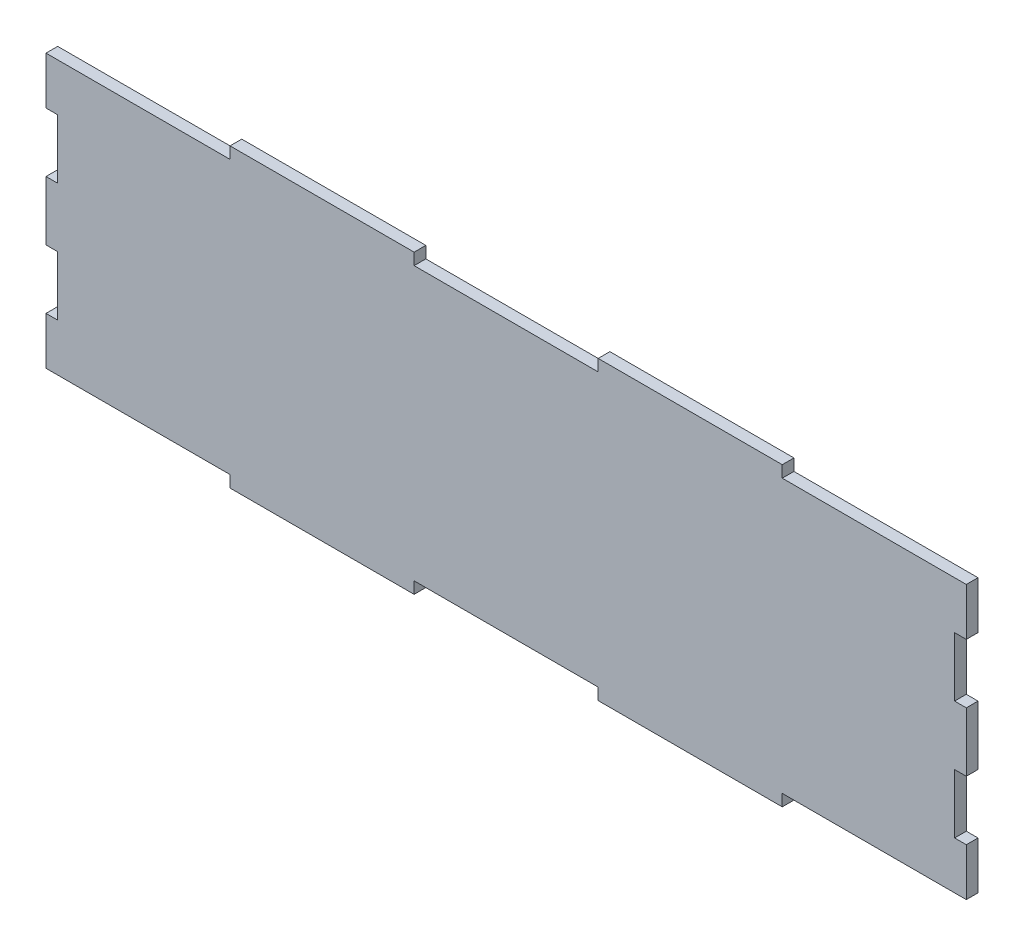
SolidWorks part; units mm, degrees
material "Pin"
ref_plane "Plan de face" through (0, 0, 0) normal (0, 0, 1) x (1, 0, 0)
ref_plane "Plan de dessus" through (0, 0, 0) normal (0, 1, 0) x (1, 0, 0)
ref_plane "Plan de droite" through (0, 0, 0) normal (1, 0, 0) x (0, 0, -1)
sketch "Esquisse1" plane through (0, 0, 0) normal (0, 0, 1) x (1, 0, 0)
  line L0 (-101.9585, 39.1998) -> (-57.7585, 39.1998)
  line L1 (-57.7585, 42.1998) -> (-10.5585, 42.1998)
  line L3 (-57.7585, -33.8002) -> (-10.5585, -33.8002)
  line L5 (128.0415, 26.9998) -> (128.0415, 11.7998)
  line L6 (-101.9585, -30.8002) -> (-57.7585, -30.8002)
  line L7 (-101.9585, 26.9998) -> (-101.9585, 11.7998)
  line L8 (-57.7585, 42.1998) -> (-57.7585, 39.1998)
  line L9 (-10.5585, -30.8002) -> (36.6415, -30.8002)
  line L10 (-10.5585, 42.1998) -> (-10.5585, 39.1998)
  line L11 (-104.9585, -33.8002) -> (131.0415, -33.8002) construction
  line L12 (36.6415, 42.1998) -> (36.6415, 39.1998)
  line L13 (36.6415, -33.8002) -> (83.8415, -33.8002)
  line L14 (83.8415, 42.1998) -> (83.8415, 39.1998)
  line L15 (-101.9585, -30.8002) -> (128.0415, -30.8002) construction
  line L16 (-104.9585, 26.9998) -> (-101.9585, 26.9998)
  line L17 (-104.9585, 11.7998) -> (-101.9585, 11.7998)
  line L18 (83.8415, -30.8002) -> (83.8415, -33.8002)
  line L19 (83.8415, -30.8002) -> (128.0415, -30.8002)
  line L20 (36.6415, -30.8002) -> (36.6415, -33.8002)
  line L21 (-104.9585, -33.8002) -> (-57.7585, -33.8002) construction
  line L22 (-10.5585, -30.8002) -> (-10.5585, -33.8002)
  line L23 (-57.7585, -30.8002) -> (-57.7585, -33.8002)
  line L24 (83.8415, -33.8002) -> (131.0415, -33.8002) construction
  line L25 (128.0415, 26.9998) -> (131.0415, 26.9998)
  line L26 (128.0415, 11.7998) -> (131.0415, 11.7998)
  line L27 (-104.9585, -3.4002) -> (-101.9585, -3.4002)
  line L28 (128.0415, -3.4002) -> (131.0415, -3.4002)
  line L29 (-104.9585, -18.6002) -> (-101.9585, -18.6002)
  line L30 (128.0415, -18.6002) -> (131.0415, -18.6002)
  line L31 (-104.9585, 26.9998) -> (-104.9585, 11.7998) construction
  line L32 (-34.1585, 47.9048) -> (-34.1585, 44.9048) [skipped]
  line L33 (13.0415, 47.9048) -> (13.0415, 44.9048) [skipped]
  line L34 (60.2415, 47.9048) -> (60.2415, 44.9048) [skipped]
  line L35 (-10.5585, 39.1998) -> (36.6415, 39.1998)
  line L36 (36.6415, 42.1998) -> (83.8415, 42.1998)
  line L37 (-101.9585, 39.1998) -> (128.0415, 39.1998) construction
  line L38 (83.8415, 39.1998) -> (128.0415, 39.1998)
  line L39 (-104.9585, 42.1998) -> (131.0415, 42.1998) construction
  line L40 (-57.7585, 42.1998) -> (-104.9585, 42.1998) construction
  line L41 (83.8415, 42.1998) -> (131.0415, 42.1998) construction
  line L42 (-104.9585, 11.7998) -> (-104.9585, -3.4002)
  line L43 (-101.9585, -3.4002) -> (-101.9585, -18.6002)
  line L44 (-104.9585, 42.1998) -> (-104.9585, -33.8002) construction
  line L46 (-101.9585, 39.1998) -> (-101.9585, -30.8002) construction
  line L47 (-101.9585, -30.8002) -> (-104.9585, -30.8002)
  line L48 (-104.9585, 42.1998) -> (-104.9585, 26.9998) construction
  line L49 (-104.9585, -18.6002) -> (-104.9585, -33.8002) construction
  line L50 (-104.9585, 26.9998) -> (-104.9585, 39.1998)
  line L51 (-104.9585, 39.1998) -> (-101.9585, 39.1998)
  line L52 (-104.9585, -30.8002) -> (-104.9585, -18.6002)
  line L53 (131.0415, 11.7998) -> (131.0415, -3.4002)
  line L54 (128.0415, 39.1998) -> (131.0415, 39.1998)
  line L55 (131.0415, 42.1998) -> (131.0415, -33.8002) construction
  line L56 (128.0415, -3.4002) -> (128.0415, -18.6002)
  line L57 (131.0415, 39.1998) -> (131.0415, 26.9998)
  line L58 (128.0415, 39.1998) -> (128.0415, -30.8002) construction
  line L59 (131.0415, -18.6002) -> (131.0415, -30.8002)
  line L60 (131.0415, -30.8002) -> (128.0415, -30.8002)
  line L61 (-104.9585, -33.8002) -> (131.0415, 42.1998) construction
  dimension "D1" = 236
  dimension "D2" = 76
  dimension "D3" = 3
  dimension "D4" = 7
  dimension "D6" = 4
extrude "Boss.-Extru.1" add sketch "Esquisse1" along normal blind 3
